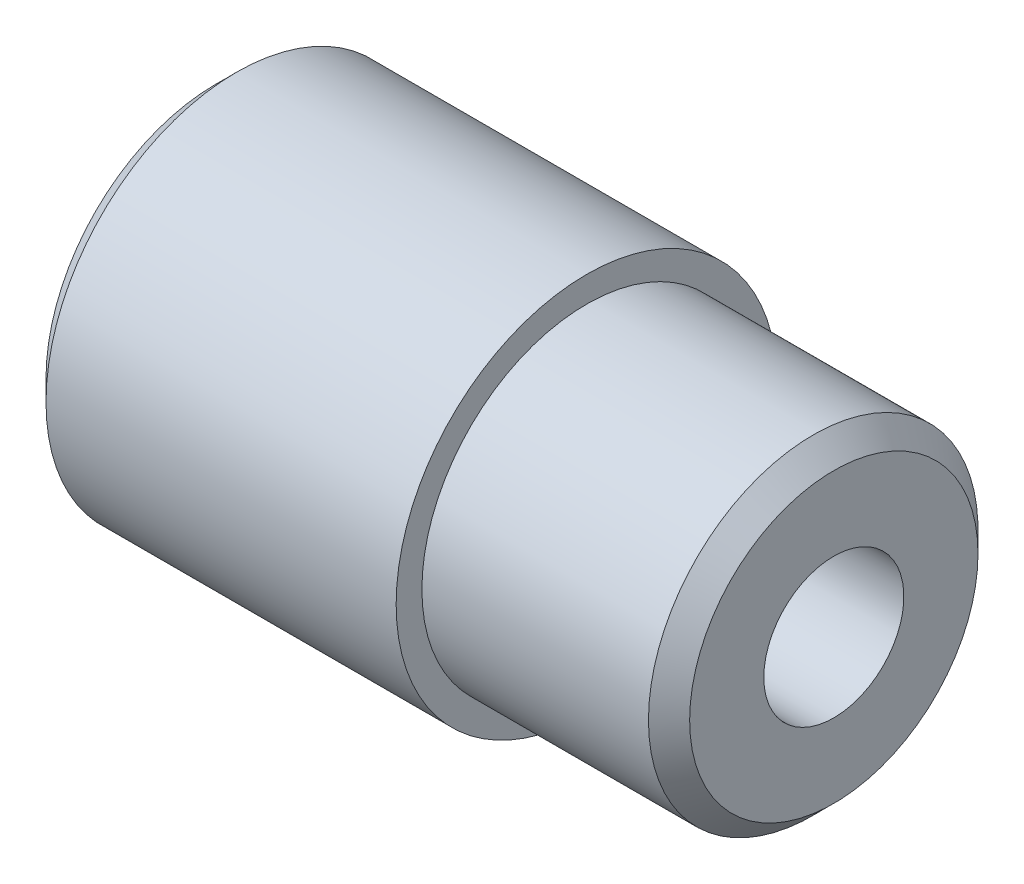
SolidWorks part; units mm, degrees
material "AISI 304"
ref_plane "Спереди" through (0, 0, 0) normal (0, 0, 1) x (1, 0, 0)
ref_plane "Сверху" through (0, 0, 0) normal (0, 1, 0) x (1, 0, 0)
ref_plane "Справа" through (0, 0, 0) normal (1, 0, 0) x (0, 0, -1)
sketch "Эскиз1" plane through (0, 0, 0) normal (0, 0, 1) x (1, 0, 0)
  line L0 (0, 0) -> (32.9251, 0) construction
  line L1 (0, 3) -> (0, 9.25)
  line L2 (0, 9.25) -> (18, 9.25)
  line L3 (18, 9.25) -> (18, 8)
  line L4 (18, 8) -> (30, 8)
  line L5 (30, 8) -> (30, 3)
  line L6 (30, 3) -> (0, 3)
  dimension "D1" = 18
  dimension "D2" = 12
  dimension "D3" = 18.5
  dimension "D4" = 16
  dimension "D5" = 6
revolve "Повернуть1" add sketch "Эскиз1" angle 360 about L0
hole_wizard "Отверстие обработанное метчиком M82" positions "Эскиз2" profile "Эскиз3" tap size "M8" standard "DIN" end condition through all
sketch "Эскиз2" plane through (0, 0, 0) normal (-1, 0, 0) x (0, 0, 1)
  point P0 (0, 0)
sketch "Эскиз3" plane through (0, 0, 0) normal (0, 1, 0) x (0, 0, 1)
  line L0 (0, 0) -> (0, 30)
  line L1 (0, 30) -> (3.4, 30)
  line L2 (3.4, 30) -> (3.4, 0)
  line L5 (3.4, 0) -> (0, 0)
  line L11 (0, -6.35) -> (0, 107.95) construction
  dimension "Диаметр проходного сверла" = 6.8
  dimension "Глубина проходного сверла" = 30
cosmetic thread "Отверстие резьбы1"
chamfer "Фаска1" distance 1 angle 45 2 edges at (0, 0, 9.25) (30, 0, 8)
